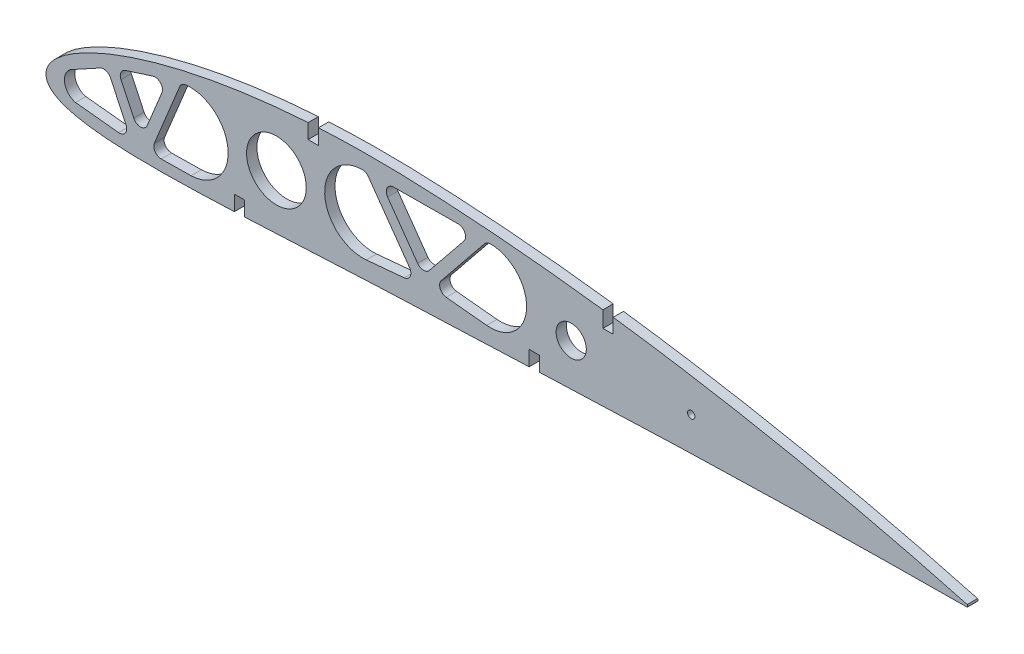
SolidWorks part; units mm, degrees
material "фанера"
ref_plane "Front" through (0, 0, 0) normal (0, 0, 1) x (1, 0, 0)
ref_plane "Top" through (0, 0, 0) normal (0, 1, 0) x (1, 0, 0)
ref_plane "Right" through (0, 0, 0) normal (1, 0, 0) x (0, 0, -1)
curve "Кривая1"
  spline degree 3 poles (0.048, 0.6214, 0) (0.0227, 0.3735, 0) (-0.0278, -0.1225, 0) (0.078, -0.8844, 0) (0.3497, -1.6388, 0) (0.8143, -2.3651, 0) (1.4635, -3.0393, 0) (2.291, -3.661, 0) (3.3059, -4.2358, 0) (4.5353, -4.7737, 0) (6.0297, -5.2822, 0) (7.869, -5.7653, 0) (10.1688, -6.2217, 0) (13.0754, -6.6396, 0) (16.7281, -6.993, 0) (21.19, -7.2473, 0) (26.4, -7.3766, 0) (32.1974, -7.3763, 0) (38.3978, -7.2614, 0) (44.8576, -7.0566, 0) (51.4865, -6.7865, 0) (58.231, -6.4723, 0) (65.0521, -6.1329, 0) (71.9108, -5.784, 0) (78.7714, -5.4397, 0) (85.6105, -5.111, 0) (92.4321, -4.805, 0) (99.255, -4.532, 0) (106.0974, -4.2783, 0) (112.9692, -4.0031, 0) (119.8644, -3.7232, 0) (126.7739, -3.4401, 0) (133.6816, -3.1587, 0) (140.5819, -2.8824, 0) (147.472, -2.6139, 0) (154.3526, -2.3556, 0) (161.225, -2.1094, 0) (168.0909, -1.8766, 0) (174.9516, -1.6586, 0) (181.8086, -1.4564, 0) (188.6632, -1.2704, 0) (195.5166, -1.1011, 0) (202.3695, -0.9486, 0) (209.2212, -0.8129, 0) (216.0668, -0.6936, 0) (222.8864, -0.5903, 0) (229.6176, -0.5029, 0) (236.0874, -0.4315, 0) (241.9808, -0.3765, 0) (246.559, -0.3395, 0) (249.1205, -0.3213, 0) (250, -0.315, 0) knots 0 0 0 0 0.002941 0.005884 0.009016 0.012365 0.016008 0.020037 0.024574 0.029784 0.035897 0.04324 0.052276 0.063635 0.077983 0.095698 0.11652 0.139661 0.164312 0.189919 0.216157 0.242838 0.269834 0.296993 0.324123 0.351139 0.378036 0.404946 0.431961 0.459078 0.486347 0.513641 0.540929 0.568176 0.59538 0.622543 0.649673 0.676775 0.703855 0.730919 0.757971 0.785018 0.812062 0.839103 0.866132 0.893099 0.919831 0.94581 0.969681 0.98959 1 1 1 1
curve "Кривая2"
  spline degree 3 poles (250, 0.315, 0) (249.1557, 0.545, 0) (246.7202, 1.2085, 0) (242.3913, 2.3583, 0) (236.8498, 3.7876, 0) (230.7799, 5.298, 0) (224.4559, 6.8129, 0) (218.0305, 8.2916, 0) (211.5624, 9.7197, 0) (205.0724, 11.0924, 0) (198.568, 12.4079, 0) (192.0524, 13.6653, 0) (185.5276, 14.8641, 0) (178.9953, 16.0034, 0) (172.4571, 17.0824, 0) (165.9143, 18.0998, 0) (159.3687, 19.0545, 0) (152.8218, 19.9449, 0) (146.2754, 20.7693, 0) (139.7314, 21.5257, 0) (133.1918, 22.212, 0) (126.6587, 22.8257, 0) (120.1368, 23.364, 0) (113.6286, 23.8247, 0) (107.1527, 24.2002, 0) (100.7411, 24.4984, 0) (94.4118, 24.6866, 0) (88.1559, 24.7401, 0) (81.949, 24.6588, 0) (75.7805, 24.441, 0) (69.6537, 24.0819, 0) (63.5754, 23.578, 0) (57.5552, 22.9249, 0) (51.6058, 22.1191, 0) (45.7444, 21.1566, 0) (39.9959, 20.0354, 0) (34.3979, 18.7563, 0) (29.0104, 17.3276, 0) (23.9258, 15.7719, 0) (19.2707, 14.1343, 0) (15.1791, 12.4833, 0) (11.7405, 10.8956, 0) (8.9594, 9.4296, 0) (6.7609, 8.1086, 0) (5.0337, 6.9246, 0) (3.6717, 5.8542, 0) (2.5921, 4.8713, 0) (1.7382, 3.9526, 0) (1.0699, 3.0809, 0) (0.5716, 2.2416, 0) (0.2158, 1.4308, 0) (0.1023, 0.8832, 0) (0.048, 0.6214, 0) knots 0 0 0 0 0.010162 0.029313 0.052012 0.076619 0.101948 0.127526 0.153184 0.178868 0.204558 0.230246 0.255926 0.281594 0.307246 0.332878 0.358485 0.384061 0.409603 0.435104 0.460559 0.485959 0.511303 0.536552 0.561723 0.586629 0.611085 0.635251 0.659272 0.683164 0.706922 0.730536 0.753983 0.777235 0.800246 0.822951 0.845237 0.866916 0.887662 0.906968 0.924203 0.938879 0.950932 0.960693 0.968647 0.975233 0.980795 0.985584 0.989782 0.993521 0.996902 1 1 1 1
sketch "Эскиз2" plane through (0, 0, 0) normal (0, 0, 1) x (1, 0, 0)
  line L0 (-1.2592, 0) -> (250.7702, 0) construction
  line L1 (250.1305, 0) -> (250.1305, 80.0888) construction
  line L2 (0, 0) -> (0, 69.7453) construction
  line L3 (62.5326, 123.1249) -> (62.5326, -48.5934) construction
  line L4 (142.5326, 131.1199) -> (142.5326, -55.0117) construction
  line L5 (62.5326, 8.5962) -> (142.5326, 8.5962) construction
  line L6 (62.5326, 8.5962) -> (150.6431, 8.5962) construction
  line L7 (175.0913, 92.567) -> (175.0913, -39.4544) construction
  line L8 (165.9405, 18.0854) -> (165.9405, -1.9504)
  line L9 (87.4969, 19.5968) -> (98.657, 3.8464)
  line L12 (107.2666, 5.069) -> (119.0427, 19.6405)
  line L13 (92.7103, 17.4282) -> (100.8475, 5.9439)
  line L14 (104.0349, 5.843) -> (113.4136, 17.4479)
  line L15 (108.6238, 1.8217) -> (119.6039, 0.7278)
  line L16 (94.3284, 20.5844) -> (111.8443, 20.705)
  line L17 (86.9285, -0.2347) -> (97.2059, 0.6983)
  line L18 (17.4887, 7.868) -> (21.7254, -1.0733)
  line L19 (29.4016, -1.5679) -> (36.2887, 15.1777)
  line L20 (20.3422, 8.8519) -> (23.813, 1.5271)
  line L21 (27.4701, 1.6228) -> (31.461, 11.3265)
  line L22 (7.9994, -2.6904) -> (19.7094, -3.9188)
  line L23 (31.2779, -4.3285) -> (39.3668, -4.221)
  line L24 (6.5801, 4.311) -> (14.7212, 8.7661)
  line L25 (21.5421, 11.6138) -> (29.0038, 13.9928)
  line L26 (72.5326, 27.406) -> (72.5326, 20.4403) construction
  line L27 (52.5326, -12.1202) -> (52.5326, -2.6904) construction
  line L28 (152.5326, 24.4982) -> (152.5326, 15.921) construction
  line L29 (132.5326, -7.5811) -> (132.5326, 3.1811) construction
  line L30 (151.1326, 20.1529) -> (151.1326, 15.7875)
  line L31 (151.1326, 15.7875) -> (153.9326, 15.7875)
  line L32 (153.9326, 15.7875) -> (153.9326, 19.7875)
  line L33 (131.1326, -3.2627) -> (131.1326, 0.8506)
  line L34 (131.1326, 0.8506) -> (133.9326, 0.8506)
  line L35 (133.9326, 0.8506) -> (133.9326, -3.1494)
  line L36 (71.1326, 24.1575) -> (71.1326, 20.1575)
  line L37 (71.1326, 20.1575) -> (73.9326, 20.1575)
  line L38 (73.9326, 20.1575) -> (73.9326, 24.3239)
  line L39 (51.1326, -6.7954) -> (51.1326, -2.6707)
  line L40 (51.1326, -2.6707) -> (53.9326, -2.6707)
  line L41 (53.9326, -2.6707) -> (53.9326, -6.6707)
  arc A0 (250, 0.315) -> (250, -0.315) centre (249.685, 0) cw
  circle A3 centre (62.5326, 8.5962) radius 8.1
  circle A5 centre (62.5326, 8.5962) radius 80 construction
  circle A6 centre (142.5326, 8.5962) radius 4.1
  arc A7 (175.0913, 16.6448) -> (175.0913, -1.657) centre (175.0913, 7.4939) ccw
  arc A10 (107.2666, 5.069) -> (108.6238, 1.8217) centre (108.8221, 3.8118) ccw
  arc A11 (85.8347, 20.4403) -> (86.9285, -0.2347) centre (85.9919, 10.0822) ccw
  arc A12 (120.6027, 20.3833) -> (119.6039, 0.7278) centre (120.5806, 10.5313) cw
  arc A13 (120.6027, 20.3833) -> (119.0427, 19.6405) centre (120.5982, 18.3834) ccw
  arc A14 (85.8347, 20.4403) -> (87.4969, 19.5968) centre (85.8651, 18.4406) cw
  arc A15 (100.8475, 5.9439) -> (104.0349, 5.843) centre (102.4794, 7.1001) ccw
  arc A16 (37.9117, 16.4041) -> (36.2887, 15.1777) centre (38.1384, 14.417) ccw
  arc A17 (98.657, 3.8464) -> (97.2059, 0.6983) centre (97.0251, 2.6901) cw
  arc A18 (92.7103, 17.4282) -> (94.3284, 20.5844) centre (94.3421, 18.5845) cw
  arc A19 (113.4136, 17.4479) -> (111.8443, 20.705) centre (111.8581, 18.7051) ccw
  arc A20 (6.5801, 4.311) -> (7.9994, -2.6904) centre (8.9558, 1.1481) ccw
  arc A21 (37.9117, 16.4041) -> (39.3668, -4.221) centre (39.0848, 6.123) cw
  arc A22 (23.813, 1.5271) -> (27.4701, 1.6228) centre (25.6204, 2.3835) ccw
  arc A23 (31.461, 11.3265) -> (29.0038, 13.9928) centre (29.6113, 12.0873) ccw
  arc A24 (20.3422, 8.8519) -> (21.5421, 11.6138) centre (22.1496, 9.7083) cw
  arc A25 (17.4887, 7.868) -> (14.7212, 8.7661) centre (15.6813, 7.0116) ccw
  arc A26 (19.7094, -3.9188) -> (21.7254, -1.0733) centre (19.9181, -1.9297) ccw
  arc A27 (29.4016, -1.5679) -> (31.2779, -4.3285) centre (31.2513, -2.3286) ccw
  circle A28 centre (175.0913, 7.4939) radius 1
  spline S0 degree 3 poles (250, 0.315) (249.1557, 0.545) (246.7202, 1.2085) (242.3913, 2.3583) (236.8498, 3.7876) (230.7799, 5.298) (224.4559, 6.8129) (218.0305, 8.2916) (211.5624, 9.7197) (205.0724, 11.0924) (198.568, 12.4079) (192.0524, 13.6653) (185.5276, 14.8641) (178.9953, 16.0034) (172.4571, 17.0824) (165.9143, 18.0998) (159.3687, 19.0545) (152.8218, 19.9449) (146.2754, 20.7693) (139.7314, 21.5257) (133.1918, 22.212) (126.6587, 22.8257) (120.1368, 23.364) (113.6286, 23.8247) (107.1527, 24.2002) (100.7411, 24.4984) (94.4118, 24.6866) (88.1559, 24.7401) (81.949, 24.6588) (75.7805, 24.441) (69.6537, 24.0819) (63.5754, 23.578) (57.5552, 22.9249) (51.6058, 22.1191) (45.7444, 21.1566) (39.9959, 20.0354) (34.3979, 18.7563) (29.0104, 17.3276) (23.9258, 15.7719) (19.2707, 14.1343) (15.1791, 12.4833) (11.7405, 10.8956) (8.9594, 9.4296) (6.7609, 8.1086) (5.0337, 6.9246) (3.6717, 5.8542) (2.5921, 4.8713) (1.7382, 3.9526) (1.0699, 3.0809) (0.5716, 2.2416) (0.2158, 1.4308) (0.1023, 0.8832) (0.048, 0.6214) knots 0 0 0 0 0.010162 0.029313 0.052012 0.076619 0.101948 0.127526 0.153184 0.178868 0.204558 0.230246 0.255926 0.281594 0.307246 0.332878 0.358485 0.384061 0.409603 0.435104 0.460559 0.485959 0.511303 0.536552 0.561723 0.586629 0.611085 0.635251 0.659272 0.683164 0.706922 0.730536 0.753983 0.777235 0.800246 0.822951 0.845237 0.866916 0.887662 0.906968 0.924203 0.938879 0.950932 0.960693 0.968647 0.975233 0.980795 0.985584 0.989782 0.993521 0.996902 1 1 1 1 construction
  spline S1 degree 3 poles (0.048, 0.6214) (0.0227, 0.3735) (-0.0278, -0.1225) (0.078, -0.8844) (0.3497, -1.6388) (0.8143, -2.3651) (1.4635, -3.0393) (2.291, -3.661) (3.3059, -4.2358) (4.5353, -4.7737) (6.0297, -5.2822) (7.869, -5.7653) (10.1688, -6.2217) (13.0754, -6.6396) (16.7281, -6.993) (21.19, -7.2473) (26.4, -7.3766) (32.1974, -7.3763) (38.3978, -7.2614) (44.8576, -7.0566) (51.4865, -6.7865) (58.231, -6.4723) (65.0521, -6.1329) (71.9108, -5.784) (78.7714, -5.4397) (85.6105, -5.111) (92.4321, -4.805) (99.255, -4.532) (106.0974, -4.2783) (112.9692, -4.0031) (119.8644, -3.7232) (126.7739, -3.4401) (133.6816, -3.1587) (140.5819, -2.8824) (147.472, -2.6139) (154.3526, -2.3556) (161.225, -2.1094) (168.0909, -1.8766) (174.9516, -1.6586) (181.8086, -1.4564) (188.6632, -1.2704) (195.5166, -1.1011) (202.3695, -0.9486) (211.4992, -0.7677) (220.6031, -0.6199) (229.6176, -0.5029) (236.0874, -0.4315) (241.9808, -0.3765) (246.559, -0.3395) (249.1205, -0.3213) (250, -0.315) knots 0 0 0 0 0.002941 0.005884 0.009016 0.012365 0.016008 0.020037 0.024574 0.029784 0.035897 0.04324 0.052276 0.063635 0.077983 0.095698 0.11652 0.139661 0.164312 0.189919 0.216157 0.242838 0.269834 0.296993 0.324123 0.351139 0.378036 0.404946 0.431961 0.459078 0.486347 0.513641 0.540929 0.568176 0.59538 0.622543 0.649673 0.676775 0.703855 0.730919 0.757971 0.785018 0.812062 0.839103 0.893099 0.919831 0.94581 0.969681 0.98959 1 1 1 1 construction
  spline S2 degree 3 poles (250, 0.315) (249.1557, 0.545) (246.7202, 1.2085) (242.3913, 2.3583) (236.8498, 3.7876) (230.7799, 5.298) (224.4559, 6.8129) (218.0305, 8.2916) (211.5624, 9.7197) (205.0724, 11.0924) (198.568, 12.4079) (192.0524, 13.6653) (185.5276, 14.8641) (178.9953, 16.0034) (172.4571, 17.0824) (165.9143, 18.0998) (159.7397, 19.0004) (155.7443, 19.5471) (153.9326, 19.7875) knots 0 0 0 0 0.010162 0.029313 0.052012 0.076619 0.101948 0.127526 0.153184 0.178868 0.204558 0.230246 0.255926 0.281594 0.307246 0.332878 0.358485 0.379707 0.379707 0.379707 0.379707
  spline S3 degree 3 poles (0.048, 0.6214) (0.0227, 0.3735) (-0.0278, -0.1225) (0.078, -0.8844) (0.3497, -1.6388) (0.8143, -2.3651) (1.4635, -3.0393) (2.291, -3.661) (3.3059, -4.2358) (4.5353, -4.7737) (6.0297, -5.2822) (7.869, -5.7653) (10.1688, -6.2217) (13.0754, -6.6396) (16.7281, -6.993) (21.19, -7.2473) (26.4, -7.3766) (32.1974, -7.3763) (38.3978, -7.2614) (44.7521, -7.06) (49.0233, -6.8868) (51.1326, -6.7954) knots 0 0 0 0 0.002941 0.005884 0.009016 0.012365 0.016008 0.020037 0.024574 0.029784 0.035897 0.04324 0.052276 0.063635 0.077983 0.095698 0.11652 0.139661 0.164312 0.189919 0.214908 0.214908 0.214908 0.214908
  spline S4 degree 3 poles (151.1326, 20.1529) (149.5127, 20.3609) (145.7129, 20.8343) (139.7314, 21.5257) (133.1918, 22.212) (126.6587, 22.8257) (120.1368, 23.364) (113.6286, 23.8247) (107.1527, 24.2002) (100.7411, 24.4984) (94.4118, 24.6866) (88.1559, 24.7401) (81.949, 24.6588) (77.2124, 24.4916) (74.545, 24.3569) (73.9326, 24.3239) knots 0.390637 0.390637 0.390637 0.390637 0.409603 0.435104 0.460559 0.485959 0.511303 0.536552 0.561723 0.586629 0.611085 0.635251 0.659272 0.683164 0.690286 0.690286 0.690286 0.690286
  spline S5 degree 3 poles (133.9326, -3.1494) (136.1503, -3.0598) (140.6644, -2.8792) (147.472, -2.6139) (154.3526, -2.3556) (161.225, -2.1094) (168.0909, -1.8766) (174.9516, -1.6586) (181.8086, -1.4564) (188.6632, -1.2704) (195.5166, -1.1011) (202.3695, -0.9486) (211.4992, -0.7677) (220.6031, -0.6199) (229.6176, -0.5029) (236.0874, -0.4315) (241.9808, -0.3765) (246.559, -0.3395) (249.1205, -0.3213) (250, -0.315) knots 0.541906 0.541906 0.541906 0.541906 0.568176 0.59538 0.622543 0.649673 0.676775 0.703855 0.730919 0.757971 0.785018 0.812062 0.839103 0.893099 0.919831 0.94581 0.969681 0.98959 1 1 1 1
  spline S6 degree 3 poles (71.1326, 24.1575) (70.636, 24.1252) (68.1106, 23.954) (63.5754, 23.578) (57.5552, 22.9249) (51.6058, 22.1191) (45.7444, 21.1566) (39.9959, 20.0354) (34.3979, 18.7563) (29.0104, 17.3276) (23.9258, 15.7719) (19.2707, 14.1343) (15.1791, 12.4833) (11.7405, 10.8956) (8.9594, 9.4296) (6.7609, 8.1086) (5.0337, 6.9246) (3.6717, 5.8542) (2.5921, 4.8713) (1.7382, 3.9526) (1.0699, 3.0809) (0.5716, 2.2416) (0.2158, 1.4308) (0.1023, 0.8832) (0.048, 0.6214) knots 0.701143 0.701143 0.701143 0.701143 0.706922 0.730536 0.753983 0.777235 0.800246 0.822951 0.845237 0.866916 0.887662 0.906968 0.924203 0.938879 0.950932 0.960693 0.968647 0.975233 0.980795 0.985584 0.989782 0.993521 0.996902 1 1 1 1
  spline S7 degree 3 poles (53.9326, -6.6707) (55.3566, -6.6057) (59.0587, -6.4311) (65.0521, -6.1329) (71.9108, -5.784) (78.7714, -5.4397) (85.6105, -5.111) (92.4321, -4.805) (99.255, -4.532) (106.0974, -4.2783) (112.9692, -4.0031) (119.8644, -3.7232) (125.9231, -3.4749) (129.6799, -3.3217) (131.1326, -3.2627) knots 0.225966 0.225966 0.225966 0.225966 0.242838 0.269834 0.296993 0.324123 0.351139 0.378036 0.404946 0.431961 0.459078 0.486347 0.513641 0.53085 0.53085 0.53085 0.53085
  point P15 (62.5326, 0)
  point P16 (142.5326, 0)
  point P21 (62.5326, 23.4501)
  point P22 (62.5326, -6.2577)
  point P26 (175.0913, 16.6448)
  point P28 (175.0913, -1.657)
  point P52 (119.6039, 20.3348)
  point P55 (86.9285, 20.3991)
  point P58 (102.3746, 3.7886)
  point P65 (100.665, 1.0123)
  point P86 (25.7497, -2.5601)
  point P88 (23.2497, -4.2901)
  point P91 (28.2497, -4.3687)
  dimension "D1" = 0.4455
  dimension "D6" = 16.2
  dimension "D7" = 160
  dimension "D9" = 8.2
  dimension "D12" = 9.1509
  dimension "D21" = 2
  dimension "D22" = 2
  dimension "D23" = 2
  dimension "D19" = 2
  dimension "D29" = 2
  dimension "D14" = 2
  dimension "D30" = 2
  dimension "D2" = 250.1305
  dimension "D3" = 62.5326
  dimension "D4" = 80
  dimension "D5" = 29.7079
  dimension "D8" = 14.8539
  dimension "D10" = 0
  dimension "D11" = 175.0913
  dimension "D13" = 67.8
  dimension "D15" = 5
  dimension "D16" = 8
  dimension "D17" = 3
  dimension "D18" = 3
  dimension "D20" = 5
  dimension "D24" = 5
  dimension "D25" = 3
  dimension "D26" = 3
  dimension "D27" = 5
  dimension "D28" = 2.5
  dimension "D31" = 10
  dimension "D32" = 10
  dimension "D33" = 10
  dimension "D34" = 10
  dimension "D35" = 2.8
  dimension "D36" = 1.4
  dimension "D37" = 4
  dimension "D38" = 2.8
  dimension "D39" = 1.4
  dimension "D40" = 4
  dimension "D41" = 2.8
  dimension "D42" = 1.4
  dimension "D43" = 4
  dimension "D44" = 1.4
  dimension "D45" = 2.8
  dimension "D46" = 4
extrude "Бобышка-Вытянуть2" add sketch "Эскиз2" along normal mid plane 2.8 contours S2 S3 L8 L20 A24 L25 A23 L21 A22 L9 A17 L17 A11 A14 A3 A6 A13 A12 L15 A10 L12 A19 L14 A15 L13 A18 L16 A26 L22 A20 L24 A25 L18 A27 L19 A16 A21 L23 | A7 S3 A0 S2 A28 | A7 S2 L8 | L8 S3 A7
equation "\"D3@Эскиз2\"=\"D2@Эскиз2\"/4"
equation "\"D8@Эскиз2\"=\"D5@Эскиз2\"/2"
equation "\"D7@Эскиз2\"=\"D4@Эскиз2\"*2"
equation "\"D11@Эскиз2\"=\"D2@Эскиз2\"*0.7"
equation "\"D28@Эскиз2\"=\"D27@Эскиз2\"/2"
